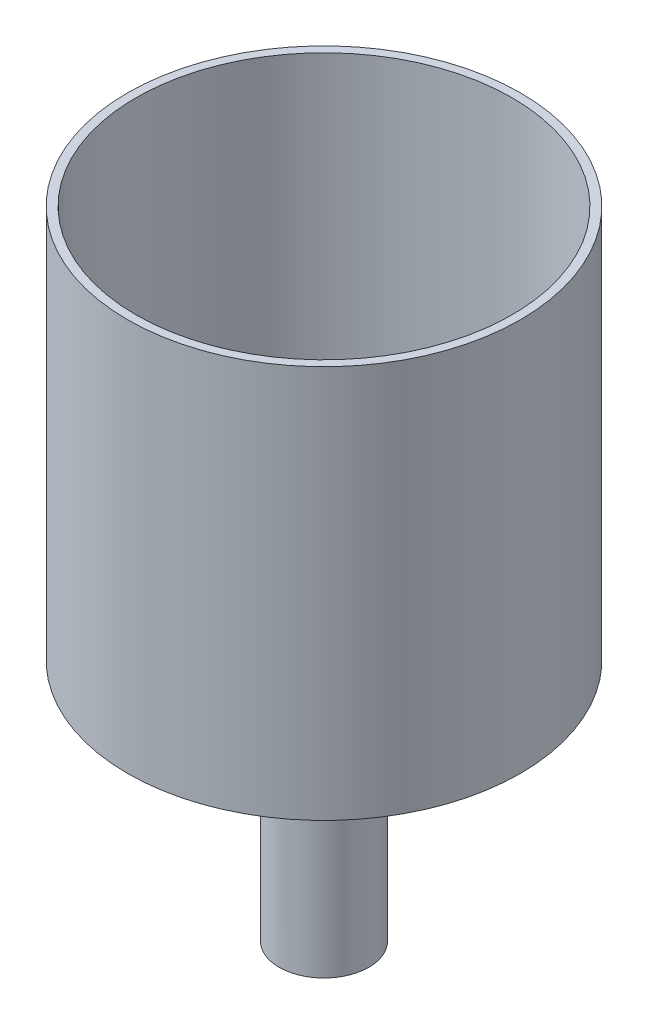
SolidWorks part; units mm, degrees
ref_plane "Front Plane" through (0, 0, 0) normal (0, 0, 1) x (1, 0, 0)
ref_plane "Top Plane" through (0, 0, 0) normal (0, 1, 0) x (1, 0, 0)
ref_plane "Right Plane" through (0, 0, 0) normal (1, 0, 0) x (0, 0, -1)
sketch "Sketch1" plane through (0, 0, 0) normal (0, 1, 0) x (1, 0, 0)
  circle A0 centre (0, 0) radius 8
  dimension "D1" = 16
extrude "Boss-Extrude1" add sketch "Sketch1" along normal blind 45
chamfer "Chamfer1" distance 3 angle 28 1 edges at (0, 0, 8)
sketch "Sketch2" plane through (0, 45, 0) normal (0, 1, 0) x (1, 0, 0)
  circle A0 centre (0, 0) radius 35
  dimension "D1" = 70
extrude "Boss-Extrude2" add sketch "Sketch2" along normal blind 70
shell "Shell1" thickness 1.5
sketch "Sketch3" plane through (0, 46.5, 0) normal (0, 1, 0) x (1, 0, 0)
  circle A0 centre (0, 0) radius 33.5
extrude "Boss-Extrude3" add sketch "Sketch3" along normal blind 2
